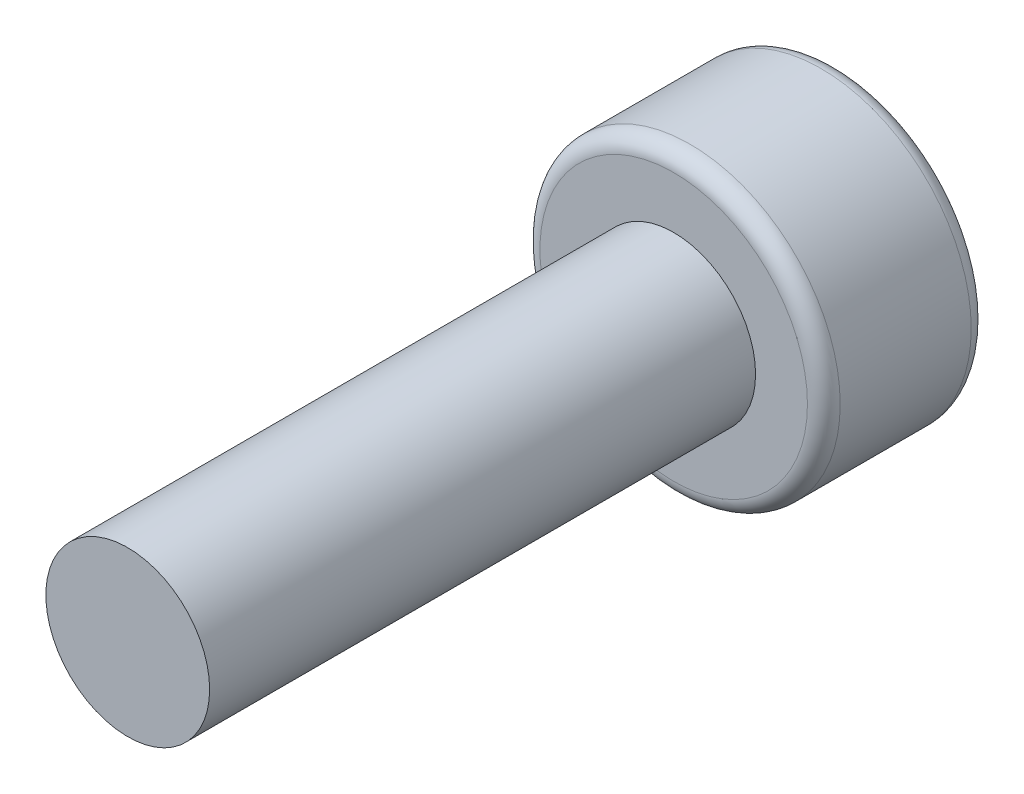
SolidWorks part; units mm, degrees
ref_plane "前视基准面" through (0, 0, 0) normal (0, 0, 1) x (1, 0, 0)
ref_plane "上视基准面" through (0, 0, 0) normal (0, 1, 0) x (1, 0, 0)
ref_plane "右视基准面" through (0, 0, 0) normal (1, 0, 0) x (0, 0, -1)
sketch "草图1" plane through (0, 0, 0) normal (0, 0, 1) x (1, 0, 0)
  circle A0 centre (0, 0) radius 2.75
  dimension "D1" = 2.75
extrude "凸台-拉伸1" add sketch "草图1" along normal blind 3
sketch "草图2" plane through (0, 0, 3) normal (0, 0, 1) x (1, 0, 0)
  circle A0 centre (0, 0) radius 1.5
  dimension "D1" = 1.5
extrude "凸台-拉伸2" add sketch "草图2" along normal blind 10
cosmetic thread "装饰螺纹线1" parameters "D2"=2
fillet "圆角1" radius 0.3 2 edges at (2.75, 0, 0) (2.75, 0, 3)
sketch "草图3" plane through (0, 0, 0) normal (0, 0, -1) x (-1, 0, 0)
  line L1 (-0.8209, 1.8624) -> (-2.0233, 0.2203)
  line L2 (-2.0233, 0.2203) -> (-1.2025, -1.6421)
  line L3 (-1.2025, -1.6421) -> (0.8209, -1.8624)
  line L4 (0.8209, -1.8624) -> (2.0233, -0.2203)
  line L5 (2.0233, -0.2203) -> (1.2025, 1.6421)
  line L6 (1.2025, 1.6421) -> (-0.8209, 1.8624)
  circle A0 centre (0, 0) radius 1.7626 construction
extrude "切除-拉伸1" cut sketch "草图3" against normal blind 2
